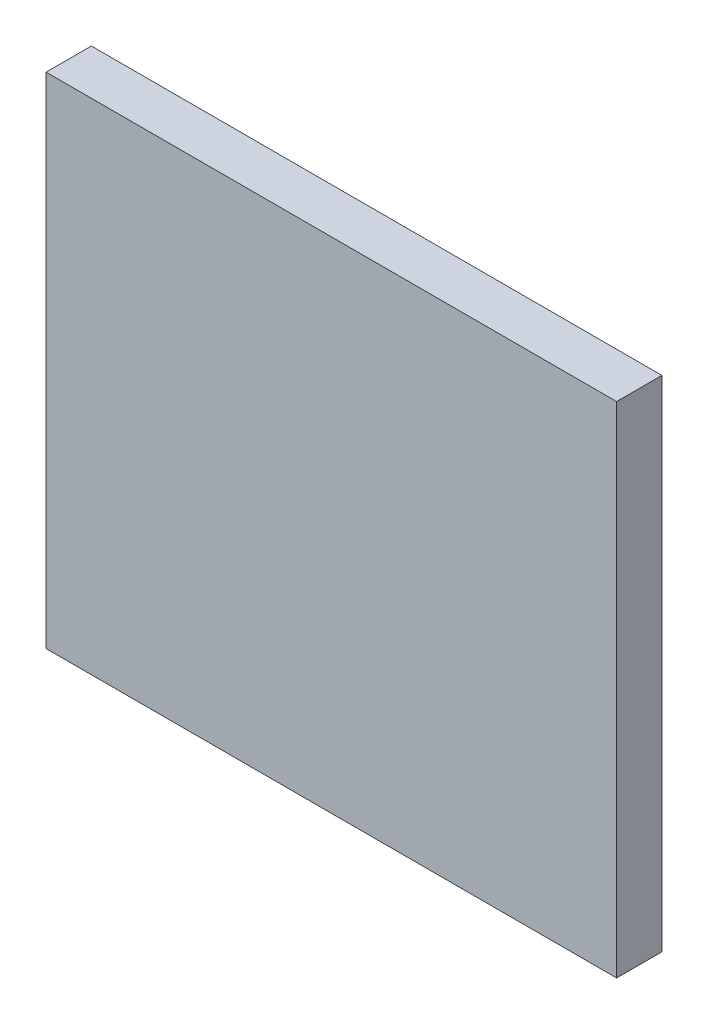
SolidWorks part; units mm, degrees
ref_plane "Front Plane" through (0, 0, 0) normal (0, 0, 1) x (1, 0, 0)
ref_plane "Top Plane" through (0, 0, 0) normal (0, 1, 0) x (1, 0, 0)
ref_plane "Right Plane" through (0, 0, 0) normal (1, 0, 0) x (0, 0, -1)
sketch "Sketch1" plane through (0, 0, 0) normal (0, 0, 1) x (1, 0, 0)
  line L1 (160, -140) -> (-160, -140)
  line L2 (160, -140) -> (160, 140)
  line L3 (160, 140) -> (-160, 140)
  line L4 (-160, -140) -> (-160, 140)
  line L5 (160, -140) -> (-160, 140) construction
  line L6 (160, 140) -> (-160, -140) construction
  point P0 (0, 0)
  dimension "D1" = 320
  dimension "D2" = 280
extrude "Boss-Extrude1" add sketch "Sketch1" along normal blind 25.4
